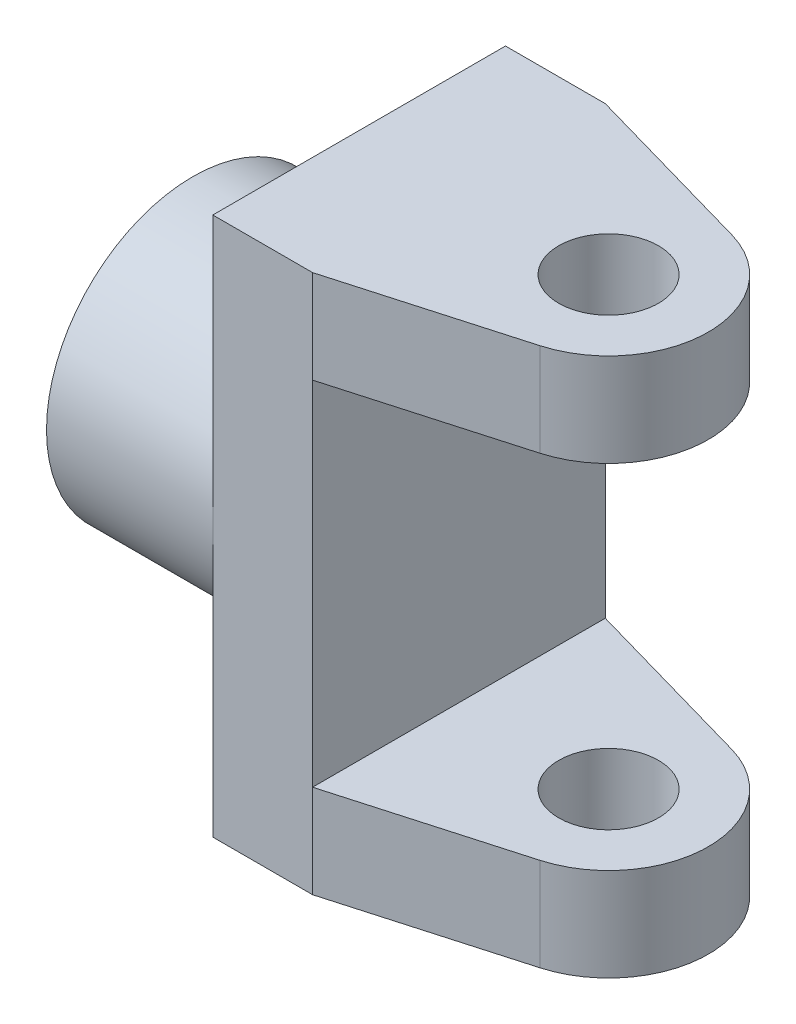
SolidWorks part; units mm, degrees
ref_plane "Front Plane" through (0, 0, 0) normal (0, 0, 1) x (1, 0, 0)
ref_plane "Top Plane" through (0, 0, 0) normal (0, 1, 0) x (1, 0, 0)
ref_plane "Right Plane" through (0, 0, 0) normal (1, 0, 0) x (0, 0, -1)
sketch "Sketch1" plane through (0, 0, 0) normal (0, 0, 1) x (1, 0, 0)
  line L4 (27.3303, 59.8073) -> (27.3303, -59.8073)
  line L7 (27.3303, 81.5086) -> (57.3303, 81.5086)
  line L8 (27.3303, 81.5086) -> (27.3303, -80.4914)
  line L9 (27.3303, -80.4914) -> (57.3303, -80.4914)
  line L10 (57.3303, 53.5086) -> (57.3303, -52.4914)
  line L11 (57.3303, 81.5086) -> (132.3303, 81.5086)
  line L13 (57.3303, 53.5086) -> (132.3303, 53.5086)
  line L14 (132.3303, 81.5086) -> (132.3303, 53.5086)
  line L15 (57.3303, -80.4914) -> (132.3303, -80.4914)
  line L17 (57.3303, -52.4914) -> (132.3303, -52.4914)
  line L18 (132.3303, -80.4914) -> (132.3303, -52.4914)
  point P0 (0, 0)
  dimension "D1" = 162
  dimension "D2" = 28
  dimension "D3" = 28
  dimension "D4" = 30
  dimension "D5" = 105
extrude "Boss-Extrude1" add sketch "Sketch1" along normal blind 88 contours L15 L18 L17 L10 L13 L14 L11 L7 L8 L4 L9
sketch "Sketch2" plane through (0, 81.5086, 0) normal (0, 1, 0) x (1, 0, 0)
  line L0 (27.3303, -88) -> (27.3303, 0) construction
  line L1 (27.3303, 0) -> (132.3303, 0) construction
  line L3 (27.3303, -88) -> (132.3303, -88) construction
  line L4 (57.3303, 0) -> (110.5431, -15.146)
  line L5 (57.3303, -88) -> (110.5431, -72.854)
  circle A0 centre (102.3303, -44) radius 15
  arc A1 (110.5431, -72.854) -> (110.5431, -15.146) centre (102.3303, -44) ccw
  line M5 (132.3303, 0) -> (27.3303, 0)
  line M7 (27.3303, -88) -> (132.3303, -88)
  line M8 (132.3303, -88) -> (132.3303, 0)
  dimension "D2" = 30
  dimension "D4" = 60
  dimension "D1" = 75
  dimension "D3" = 44
extrude "Cut-Extrude1" cut sketch "Sketch2" against normal through all contours A1 L4 M8 M5 | A1 L5 M7 M8
sketch "Sketch3" plane through (0, 81.5086, 0) normal (0, 1, 0) x (1, 0, 0)
  line L0 (27.3303, -88) -> (27.3303, 0) construction
  circle A0 centre (102.3303, -44) radius 15
  dimension "D1" = 30
  dimension "D2" = 75
extrude "Cut-Extrude2" cut sketch "Sketch3" against normal through all
sketch "Sketch4" plane through (27.3303, 0, 0) normal (-1, 0, 0) x (0, 0, 1)
  line L0 (0, 81.5086) -> (0, -80.4914) construction
  line L1 (24.4041, 4.5086) -> (20.4041, 4.5086)
  line L3 (24.4041, -3.4914) -> (20.4041, -3.4914)
  line L4 (20.4041, 4.5086) -> (20.4041, -3.4914)
  line L7 (88, 81.5086) -> (0, 81.5086) construction
  circle A0 centre (44, 0.5086) radius 44
  arc A1 (24.4041, -3.4914) -> (24.4041, 4.5086) centre (44, 0.5086) ccw
  point P3 (27.164, 0.5086)
  dimension "D1" = 88
  dimension "D2" = 40
  dimension "D3" = 8
  dimension "D4" = 81
  dimension "D5" = 4
extrude "Boss-Extrude3" add sketch "Sketch4" along normal blind 50 contours A0 | A1 L1 L4 L3
scale "Scale1" scale about centroid uniform scaling yes scale factor 0.3
